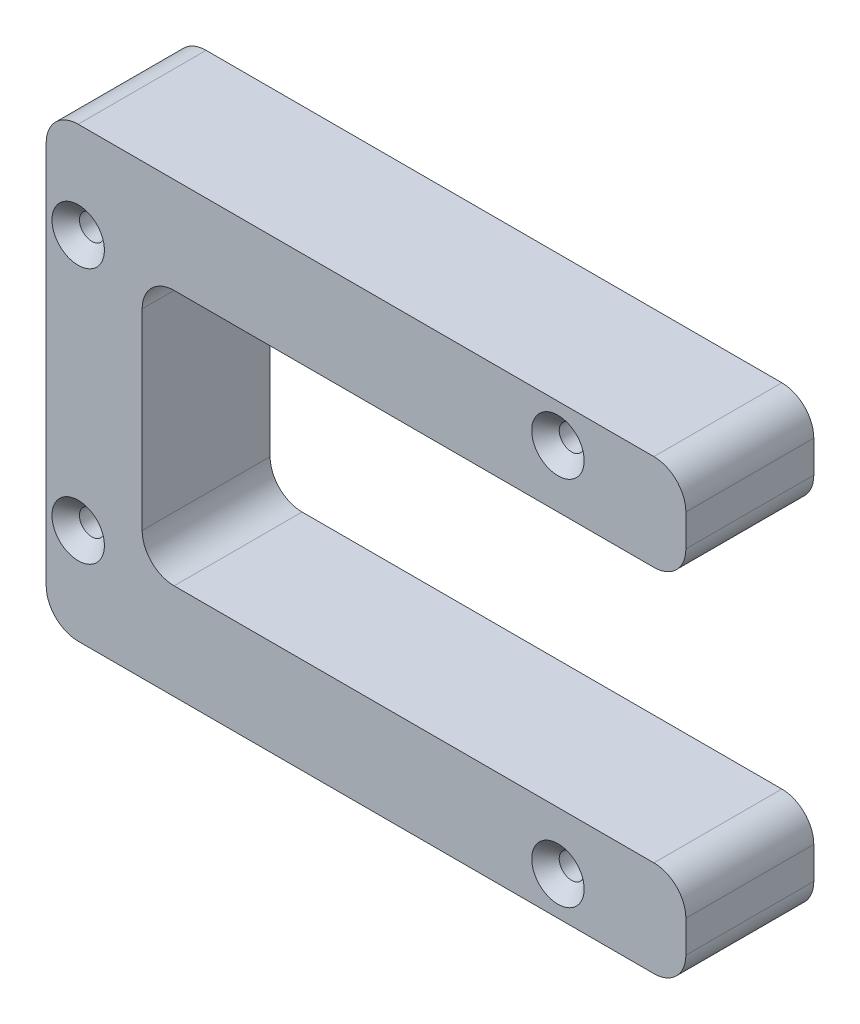
SolidWorks part; units mm, degrees
ref_plane "Piano frontale" through (0, 0, 0) normal (1, 0, 0) x (0, 1, 0)
ref_plane "Piano superiore" through (0, 0, 0) normal (0, 0, 1) x (0, 1, 0)
ref_plane "Piano destro" through (0, 0, 0) normal (0, 1, 0) x (-1, 0, 0)
ref_plane "Alzata" through (0, 0, 50) normal (0, 0, 1) x (0, 1, 0)
ref_plane "Base" through (0, 0, 20) normal (0, 0, 1) x (0, 1, 0)
sketch "Schizzo1" plane through (0, 0, 0) normal (0, 0, 1) x (0, 1, 0)
  line L1 (-35, -50) -> (35, -50)
  line L2 (-35, -50) -> (-35, 50)
  line L3 (-35, 50) -> (35, 50)
  line L4 (35, -50) -> (35, 50)
  line L5 (-35, -50) -> (35, 50) construction
  line L6 (-35, 50) -> (35, -50) construction
  point P0 (0, 0)
  dimension "D1" = 70
  dimension "D2" = 100
extrude "Estrusione-Estrusione1" add sketch "Schizzo1" along normal blind 20
sketch "Schizzo6" plane through (0, 0, 20) normal (0, 0, 1) x (1, 0, 0)
  line L0 (-50, -35) -> (50, -35) construction
  line L1 (-50, 35) -> (-50, -35) construction
  line L2 (50, -35) -> (50, 35) construction
  point P0 (-45, -20)
  point P1 (30, -29)
  dimension "D1" = 15
  dimension "D2" = 5
  dimension "D3" = 6
  dimension "D4" = 20
hole_wizard "Foro svasato per Vite M3.5-2" positions "Schizzo6" profile "Schizzo7" countersink size "M3.5" standard "Ansi Metric" end condition through all
sketch "Schizzo7" plane through (-45, -20, 20) normal (1, 0, 0) x (0, -1, 0)
  line L0 (0, 0) -> (0, 20)
  line L1 (0, 20) -> (1.95, 20)
  line L2 (1.95, 20) -> (1.95, 2.15)
  line L3 (1.95, 2.15) -> (4.1, 0)
  line L5 (4.1, 0) -> (0, 0)
  line L6 (-1.95, 2.15) -> (-4.1, 0) construction
  line L11 (0, -6.35) -> (0, 107.95) construction
  dimension "Thru Hole Dia." = 3.9
  dimension "Thru Hole Depth" = 20
  dimension "Near C'Sink Dia." = 8.2
  dimension "Near C'Sink Angle" = 90
mirror "Specchia1" about plane through (0, 0, 0) normal (0, 1, 0) of "Foro svasato per Vite M3.5-2"
sketch "Schizzo8" plane through (0, 0, 20) normal (0, 0, 1) x (1, 0, 0)
  line L6 (50, -35) -> (50, 35) construction
  line L7 (50, 20) -> (-35, 20)
  line L8 (50, 20) -> (50, -20)
  line L9 (50, -20) -> (-35, -20)
  line L10 (-35, 20) -> (-35, -20)
  line L11 (-50, 35) -> (-50, -35) construction
  line L12 (50, 35) -> (-50, 35) construction
  point P6 (50, 0)
  dimension "D1" = 15
  dimension "D2" = 15
extrude "Taglio-Estrusione1" cut sketch "Schizzo8" against normal through all
fillet "Raccordo2" radius 5 8 edges at (50, -35, 10) (-50, -35, 10) (-50, 35, 10) (50, 35, 10) (50, 20, 10) (-35, 20, 10) (-35, -20, 10) (50, -20, 10)
